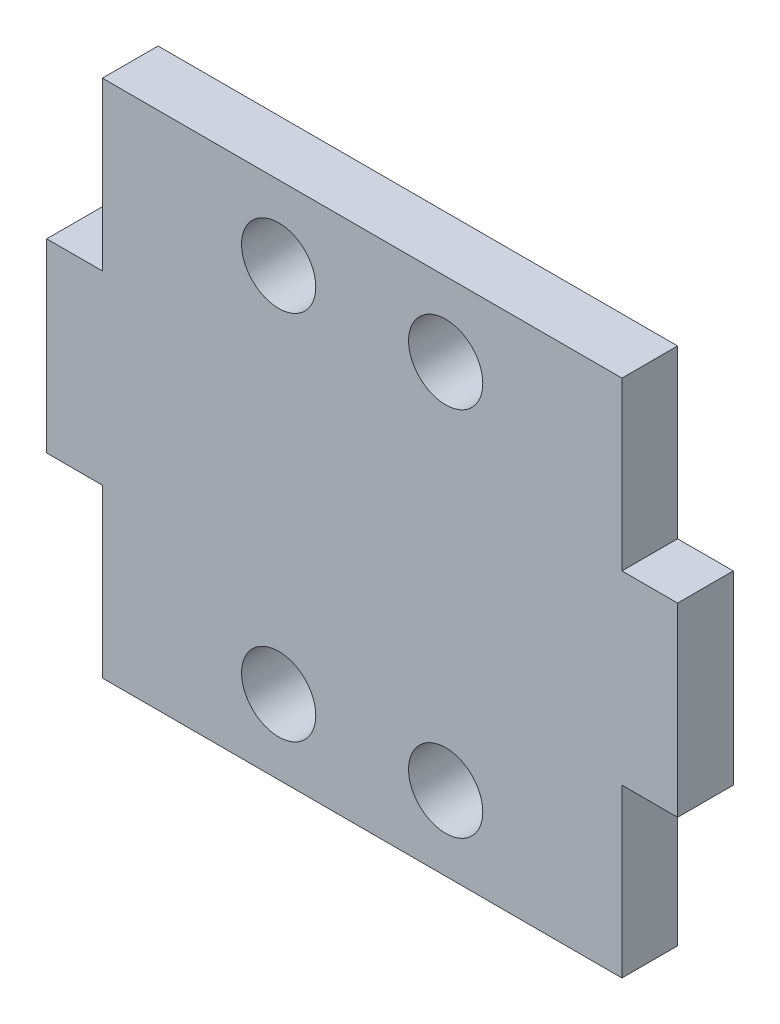
SolidWorks part; units mm, degrees
material "Plain Carbon Steel"
ref_plane "Front Plane" through (0, 0, 0) normal (0, 0, 1) x (1, 0, 0)
ref_plane "Top Plane" through (0, 0, 0) normal (0, 1, 0) x (1, 0, 0)
ref_plane "Right Plane" through (0, 0, 0) normal (1, 0, 0) x (0, 0, -1)
sketch "Sketch1" plane through (0, 0, 0) normal (0, 0, 1) x (1, 0, 0)
  line L1 (-14, -14) -> (14, -14)
  line L2 (-14, -14) -> (-14, -5)
  line L3 (-14, 14) -> (14, 14)
  line L4 (14, -14) -> (14, -5)
  line L6 (0, 14) -> (0, 0) construction
  line L7 (-14, 5) -> (-17, 5)
  line L8 (-17, 5) -> (-17, -5)
  line L9 (-17, -5) -> (-14, -5)
  line L10 (-14, 5) -> (-14, 14)
  line L11 (17, -5) -> (14, -5)
  line L12 (17, 5) -> (17, -5)
  line L13 (14, 5) -> (17, 5)
  line L14 (14, 5) -> (14, 14)
  circle A0 centre (-4.5, 10) radius 2
  circle A1 centre (4.5, 10) radius 2
  circle A3 centre (-4.5, -10) radius 2
  circle A4 centre (4.5, -10) radius 2
  point P20 (-17, 0)
  dimension "D3" = 4
  dimension "D5" = 4
  dimension "D8" = 4
  dimension "D9" = 4
  dimension "D1" = 28
  dimension "D2" = 9.5
  dimension "D4" = 9.5
  dimension "D6" = 4
  dimension "D7" = 4
  dimension "D10" = 4
  dimension "D11" = 28
  dimension "D12" = 4
  dimension "D15" = 3
  dimension "D13" = 10
  dimension "D14" = 9
extrude "Boss-Extrude1" add sketch "Sketch1" along normal blind 3 contours A3 | A4 | A1 | A0 | L3 L14 L13 L12 L11 L4 L1 L2 L9 L8 L7 L10
equation "\"D14@Sketch1\"=(\"D11@Sketch1\"-\"D13@Sketch1\")/2"
